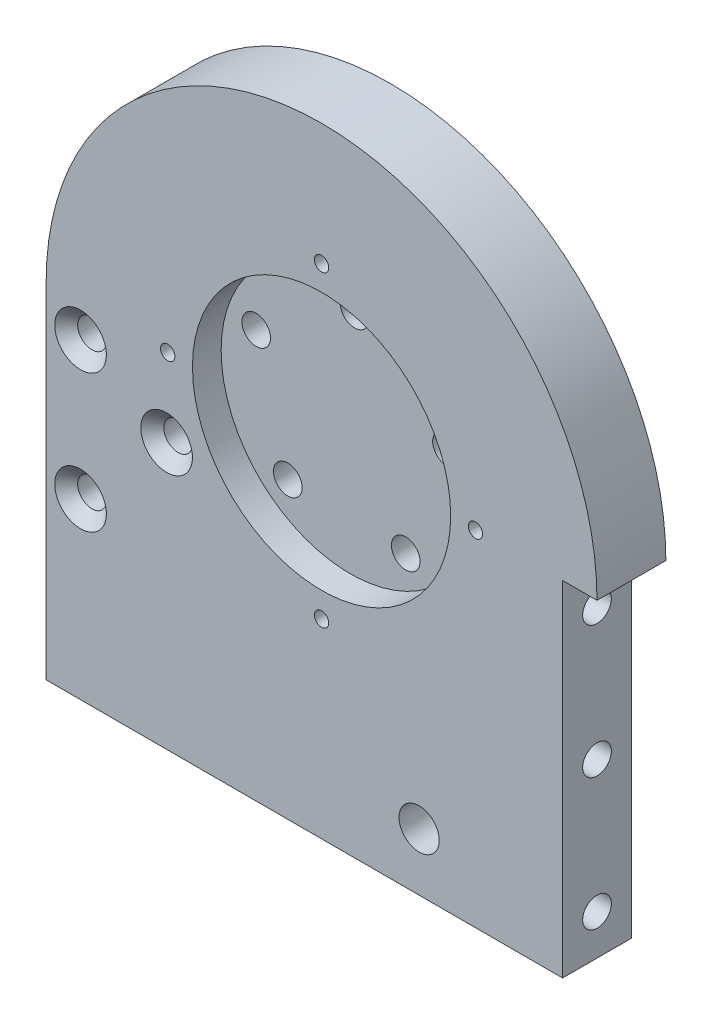
SolidWorks part; units mm, degrees
material "AISI 316 Stainless Steel Sheet (SS)"
ref_plane "Front Plane" through (0, 0, 0) normal (0, 0, 1) x (1, 0, 0)
ref_plane "Top Plane" through (0, 0, 0) normal (0, 1, 0) x (1, 0, 0)
ref_plane "Right Plane" through (0, 0, 0) normal (1, 0, 0) x (0, 0, -1)
sketch "Sketch1" plane through (0, 0, 0) normal (0, 0, 1) x (1, 0, 0)
  line L0 (45, 30) -> (51, 30)
  line L1 (-45, -30) -> (45, -30)
  line L2 (-45, -30) -> (-45, 30)
  line L4 (45, -30) -> (45, 30)
  line L5 (-45, -30) -> (45, 30) construction
  line L6 (-45, 30) -> (45, -30) construction
  arc A0 (-45, 30) -> (51, 30) centre (3, 30) cw
  point P0 (0, 0)
  dimension "D1" = 60
  dimension "D2" = 90
  dimension "D3" = 6
extrude "Boss-Extrude1" add sketch "Sketch1" along normal blind 12
sketch "Sketch2" plane through (0, 0, 12) normal (0, 0, 1) x (1, 0, 0)
  circle A0 centre (3, 30) radius 22.5
  dimension "D1" = 45
extrude "Cut-Extrude1" cut sketch "Sketch2" against normal blind 5
sketch "Sketch3" plane through (0, 0, 7) normal (0, 0, 1) x (1, 0, 0)
  circle A0 centre (3.7516, 47.4839) radius 2.5
  circle A1 centre (3, 30) radius 22.5 construction
  dimension "D1" = 5
  dimension "D2" = 17.5
extrude "Cut-Extrude2" cut sketch "Sketch3" against normal through all
pattern_circular "CirPattern1" count 5 over 360 about axis through (3, 30, 0) along (0, 0, 1) of "Cut-Extrude2"
sketch "Sketch4" plane through (0, 0, 12) normal (0, 0, 1) x (1, 0, 0)
  circle A0 centre (3, 56.8136) radius 1.25
  dimension "D1" = 2.5
extrude "Cut-Extrude3" cut sketch "Sketch4" against normal through all
pattern_circular "CirPattern2" count 4 over 360 about axis through (3, 30, 0) along (0, 0, 1) of "Cut-Extrude3"
sketch "Sketch11" plane through (0, 0, 12) normal (0, 0, 1) x (1, 0, 0)
  line L0 (-45, -30) -> (45, -30) construction
  line L2 (45, -30) -> (45, 30) construction
  circle A0 centre (20, -20) radius 3.5
  dimension "D1" = 7
  dimension "D2" = 10
  dimension "D3" = 25
extrude "Cut-Extrude8" cut sketch "Sketch11" against normal blind 14.5
sketch "Sketch13" plane through (0, -30, 0) normal (0, -1, 0) x (1, 0, 0)
  line L0 (-45, 12) -> (-45, 0) construction
  line L1 (-45, 0) -> (45, 0) construction
  circle A0 centre (-36.7, 5.2) radius 3.25
  dimension "D1" = 6.5
  dimension "D2" = 8.3
  dimension "D3" = 5.2
extrude "Cut-Extrude9" cut sketch "Sketch13" against normal blind 8
pattern_linear "LPattern2" count 2 spacing 28.2 along (1, 0, 0) of "Cut-Extrude9"
sketch "Sketch14" plane through (45, 0, 0) normal (1, 0, 0) x (0, 0, -1)
  line L0 (-12, -30) -> (0, -30) construction
  line L1 (0, -30) -> (0, 30) construction
  circle A0 centre (-6, -23) radius 2.5
  dimension "D1" = 5
  dimension "D2" = 7
  dimension "D3" = 6
extrude "Cut-Extrude10" cut sketch "Sketch14" against normal blind 8
pattern_linear "LPattern3" count 3 spacing 23 along (0, 1, 0) of "Cut-Extrude10"
hole_wizard "CSK for M5 Flat Head Machine Screw1" positions "Sketch17" profile "Sketch18" countersink size "M5" standard "ANSI Metric" end condition up to next
sketch "Sketch17" plane through (0, 0, 12) normal (0, 0, 1) x (1, 0, 0)
  line L0 (-45, 30) -> (-45, -30) construction
  point P0 (-39, 24.3)
  point P2 (-39, 0.3)
  point P13 (-24, 16.3)
  dimension "D1" = 5.7
  dimension "D2" = 24
  dimension "D3" = 15
  dimension "D4" = 16
  dimension "D5" = 6
sketch "Sketch18" plane through (-39, 24.3, 12) normal (1, 0, 0) x (0, -1, 0)
  line L0 (0, 0) -> (0, 12)
  line L1 (0, 12) -> (2.5, 12)
  line L2 (2.5, 12) -> (2.5, 2)
  line L3 (2.5, 2) -> (4.5, 0)
  line L5 (4.5, 0) -> (0, 0)
  line L6 (-2.5, 2) -> (-4.5, 0) construction
  line L11 (0, -6.35) -> (0, 107.95) construction
  dimension "Thru Hole Dia." = 5
  dimension "Thru Hole Depth" = 12
  dimension "Near C'Sink Dia." = 9
  dimension "Near C'Sink Angle" = 90
